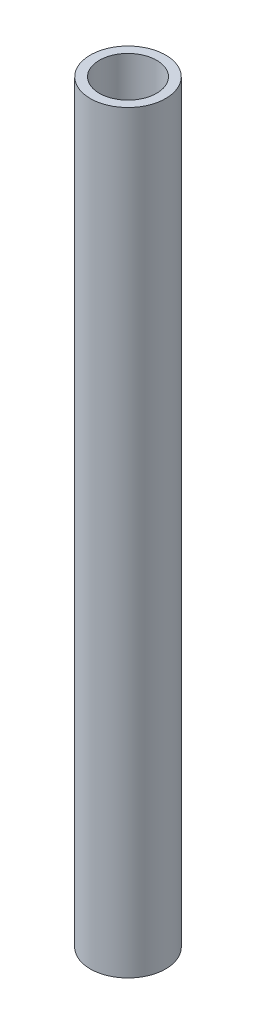
SolidWorks part; units mm, degrees
ref_plane "前视基准面" through (0, 0, 0) normal (0, 0, 1) x (1, 0, 0)
ref_plane "上视基准面" through (0, 0, 0) normal (0, 1, 0) x (1, 0, 0)
ref_plane "右视基准面" through (0, 0, 0) normal (1, 0, 0) x (0, 0, -1)
sketch "草图1" plane through (0, 0, 0) normal (0, 1, 0) x (1, 0, 0)
  circle A0 centre (0, 0) radius 5
  circle A1 centre (0, 0) radius 3.8
  dimension "D1" = 10
  dimension "D2" = 1.2
extrude "凸台-拉伸1" add sketch "草图1" along normal blind 100
